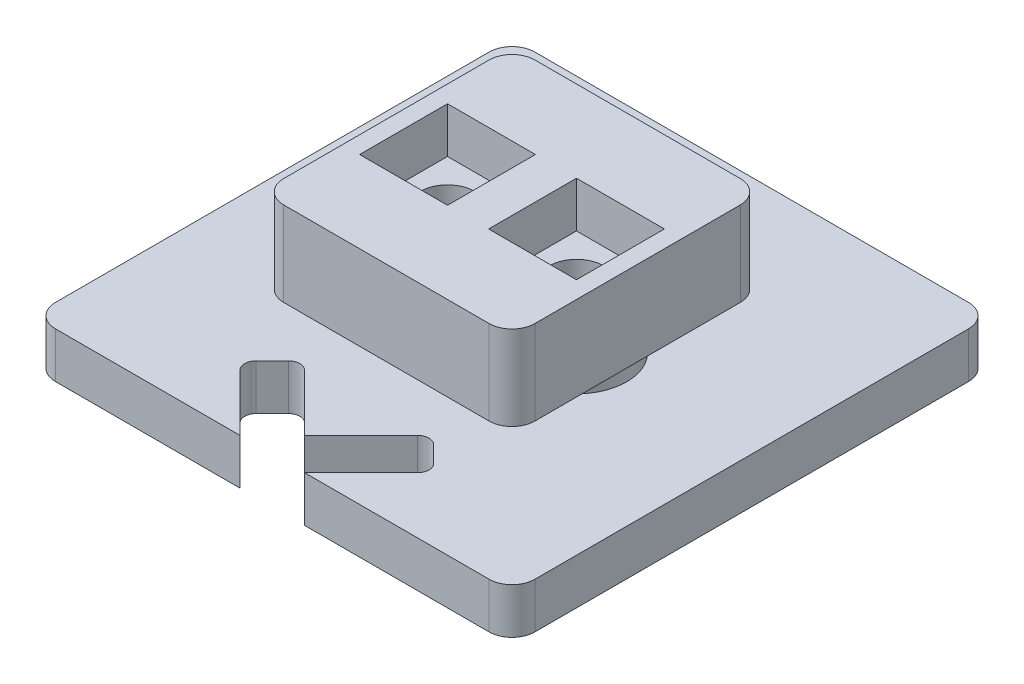
SolidWorks part; units mm, degrees
ref_plane "Front Plane" through (0, 0, 0) normal (0, 0, 1) x (1, 0, 0)
ref_plane "Top Plane" through (0, 0, 0) normal (0, 1, 0) x (1, 0, 0)
ref_plane "Right Plane" through (0, 0, 0) normal (1, 0, 0) x (0, 0, -1)
sketch "Sketch1" plane through (0, 0, 0) normal (0, 1, 0) x (1, 0, 0)
  line L1 (-5.5, -5.5) -> (5.5, -5.5)
  line L2 (-5.5, -5.5) -> (-5.5, 5.5)
  line L3 (-5.5, 5.5) -> (5.5, 5.5)
  line L4 (5.5, -5.5) -> (5.5, 5.5)
  line L5 (-5.5, -5.5) -> (5.5, 5.5) construction
  line L6 (-5.5, 5.5) -> (5.5, -5.5) construction
  point P0 (0, 0)
  dimension "D1" = 11
  dimension "D2" = 11
extrude "Boss-Extrude1" add sketch "Sketch1" along normal blind 3.7
fillet "Fillet1" radius 1 4 edges at (-5.5, 1.85, -5.5) (-5.5, 1.85, 5.5) (5.5, 1.85, -5.5) (5.5, 1.85, 5.5)
sketch "Sketch2" plane through (0, 3.7, 0) normal (0, 1, 0) x (1, 0, 0)
  line L0 (-2.825, 0) -> (2.825, 0) construction
  line L2 (-4.75, -1.925) -> (-0.9, -1.925)
  line L3 (-4.75, -1.925) -> (-4.75, 1.925)
  line L4 (-4.75, 1.925) -> (-0.9, 1.925)
  line L5 (-0.9, -1.925) -> (-0.9, 1.925)
  line L6 (-4.75, -1.925) -> (-0.9, 1.925) construction
  line L7 (-4.75, 1.925) -> (-0.9, -1.925) construction
  line L8 (0.9, -1.925) -> (4.75, -1.925)
  line L9 (0.9, -1.925) -> (0.9, 1.925)
  line L10 (0.9, 1.925) -> (4.75, 1.925)
  line L11 (4.75, -1.925) -> (4.75, 1.925)
  line L12 (0.9, -1.925) -> (4.75, 1.925) construction
  line L13 (0.9, 1.925) -> (4.75, -1.925) construction
  point P4 (0, 0)
  dimension "D1" = 3.85
  dimension "D2" = 3.85
  dimension "D3" = 3.85
  dimension "D4" = 3.85
  dimension "D5" = 5.65
extrude "Cut-Extrude1" cut sketch "Sketch2" against normal blind 2
sketch "Sketch4" plane through (0, 0, 0) normal (0, -1, 0) x (-1, 0, 0)
  line L0 (2.825, 0) -> (-2.825, 0) construction
  circle A0 centre (2.825, 0) radius 2.2
  circle A1 centre (-2.825, 0) radius 2.2
  point P4 (0, 0)
  point P8 (0, 0)
  dimension "D1" = 5.65
  dimension "D2" = 4.4
  dimension "D3" = 4.4
extrude "Boss-Extrude2" add sketch "Sketch4" along normal blind 3
sketch "Sketch5" plane through (0, -3, 0) normal (0, -1, 0) x (-1, 0, 0)
  line L1 (9.5, 10.5) -> (-9.5, 10.5)
  line L2 (10.5, 9.5) -> (10.5, -9.5)
  line L3 (9.5, -10.5) -> (-9.5, -10.5)
  line L4 (-10.5, 9.5) -> (-10.5, -9.5)
  line L5 (10.5, 10.5) -> (-10.5, -10.5) construction
  line L6 (10.5, -10.5) -> (-10.5, 10.5) construction
  arc A0 (10.5, -9.5) -> (9.5, -10.5) centre (9.5, -9.5) cw
  arc A1 (-10.5, -9.5) -> (-9.5, -10.5) centre (-9.5, -9.5) ccw
  arc A2 (-9.5, 10.5) -> (-10.5, 9.5) centre (-9.5, 9.5) ccw
  arc A3 (9.5, 10.5) -> (10.5, 9.5) centre (9.5, 9.5) cw
  point P0 (0, 0)
  dimension "D3" = 1
  dimension "D1" = 21
  dimension "D2" = 21
extrude "Boss-Extrude3" add sketch "Sketch5" against normal blind 2
sketch "Sketch3" plane through (0, 3.7, 0) normal (0, 1, 0) x (1, 0, 0)
  line L0 (-2.825, 0) -> (2.825, 0) construction
  circle A0 centre (-2.825, 0) radius 1.2
  circle A1 centre (2.825, 0) radius 1.2
  point P4 (0, 0)
  point P5 (0, 0)
  point P8 (0, 0)
  dimension "D2" = 2.4
  dimension "D3" = 2.4
  dimension "D1" = 5.65
extrude "Cut-Extrude2" cut sketch "Sketch3" against normal through all
sketch "Sketch7" plane through (0, -1, 0) normal (0, 1, 0) x (1, 0, 0)
  line L0 (9.5, -10.5) -> (-9.5, -10.5) construction
  line L1 (2.8284, -14.7426) -> (4.2426, -13.3284)
  line L2 (2.8284, -14.7426) -> (-3.8891, -8.0251)
  line L3 (-3.8891, -7.318) -> (-3.182, -6.6109)
  line L4 (4.2426, -13.3284) -> (-2.4749, -6.6109)
  line L5 (2.8284, -14.7426) -> (-2.8284, -6.2574) construction
  line L6 (-4.2426, -7.6716) -> (4.2426, -13.3284) construction
  line L8 (-4.2426, -13.3284) -> (-2.8284, -14.7426)
  line L9 (-4.2426, -13.3284) -> (2.4749, -6.6109)
  line L10 (3.182, -6.6109) -> (3.8891, -7.318)
  line L11 (-2.8284, -14.7426) -> (3.8891, -8.0251)
  line L12 (-4.2426, -13.3284) -> (4.2426, -7.6716) construction
  line L13 (2.8284, -6.2574) -> (-2.8284, -14.7426) construction
  arc A0 (-2.4749, -6.6109) -> (-3.182, -6.6109) centre (-2.8284, -6.9645) ccw
  arc A1 (3.8891, -7.318) -> (3.8891, -8.0251) centre (3.5355, -7.6716) cw
  arc A2 (3.182, -6.6109) -> (2.4749, -6.6109) centre (2.8284, -6.9645) ccw
  arc A3 (-3.8891, -7.318) -> (-3.8891, -8.0251) centre (-3.5355, -7.6716) ccw
  point P0 (0, -10.5)
  point P7 (0, -10.5)
  point P12 (-1.4142, -10.5)
  point P13 (1.4142, -10.5)
  line M12 (-9.5, -10.5) -> (9.5, -10.5)
  dimension "D7" = 0.5
  dimension "D8" = 0.5
  dimension "D1" = 2
  dimension "D2" = 45
  dimension "D3" = 2
  dimension "D4" = 45
  dimension "D5" = 4
  dimension "D6" = 4
extrude "Cut-Extrude3" cut sketch "Sketch7" against normal through all contours L10 A2 L9 L4 L11 A1 | L3 A3 L2 L9 L4 A0 | L9 L4 M12
equation "\"D2@Sketch2\"=\"D1@Sketch2\""
equation "\"D3@Sketch2\"=\"D1@Sketch2\""
equation "\"D4@Sketch2\"=\"D1@Sketch2\""
equation "\"D2@Sketch1\"=\"D1@Sketch1\""
equation "\"D3@Sketch3\"=\"D2@Sketch3\""
equation "\"D3@Sketch4\"=\"D2@Sketch4\""
equation "\"D2@Sketch5\"=\"D1@Sketch5\""
equation "\"D3@Sketch7\"=\"D1@Sketch7\""
equation "\"D6@Sketch7\"=\"D5@Sketch7\""
